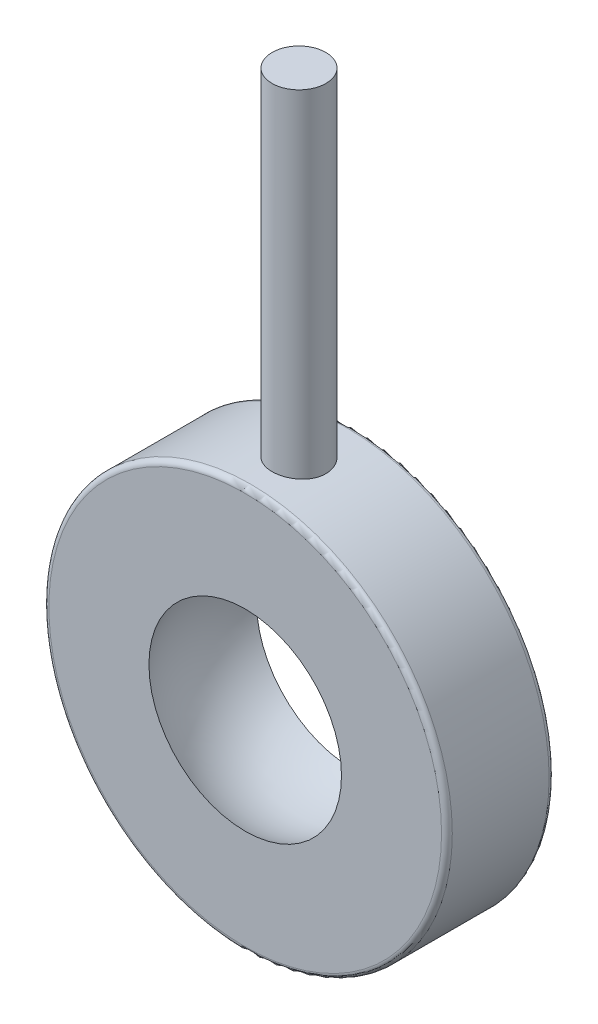
SolidWorks part; units mm, degrees
ref_plane "Front Plane" through (0, 0, 0) normal (0, 0, 1) x (1, 0, 0)
ref_plane "Top Plane" through (0, 0, 0) normal (0, 1, 0) x (1, 0, 0)
ref_plane "Right Plane" through (0, 0, 0) normal (1, 0, 0) x (0, 0, -1)
sketch "Sketch1" plane through (0, 0, 0) normal (0, 0, 1) x (1, 0, 0)
  line L0 (0, -136.9355) -> (0, 136.9355) construction
  circle A2 centre (0, 0) radius 75
  point P6 (0, 0)
  dimension "Socket_OD" = 150
sketch "Sketch3" plane through (0, 0, 0) normal (0, 1, 0) x (1, 0, 0)
  circle A0 centre (0, 0) radius 10
  dimension "Handle_OD" = 20
extrude "Boss-Extrude2" add sketch "Sketch1" along normal mid plane 40
extrude "Boss-Extrude3" add sketch "Sketch3" along normal blind 200
fillet "Fillet1" radius 2 2 edges at (75, 0, 20) (75, 0, -20)
sketch "Sketch4" plane through (0, 0, 0) normal (0, 0, 1) x (1, 0, 0)
  line L0 (0, -93.5298) -> (0, 93.5298) construction
  line L1 (0, 41.005) -> (0, -41.005)
  arc A0 (0, 41.005) -> (0, -41.005) centre (0, 0) ccw
  point P6 (0, 0)
  dimension "D1" = 82.01
revolve "Cut-Revolve1" cut sketch "Sketch4" angle 360 about L0
